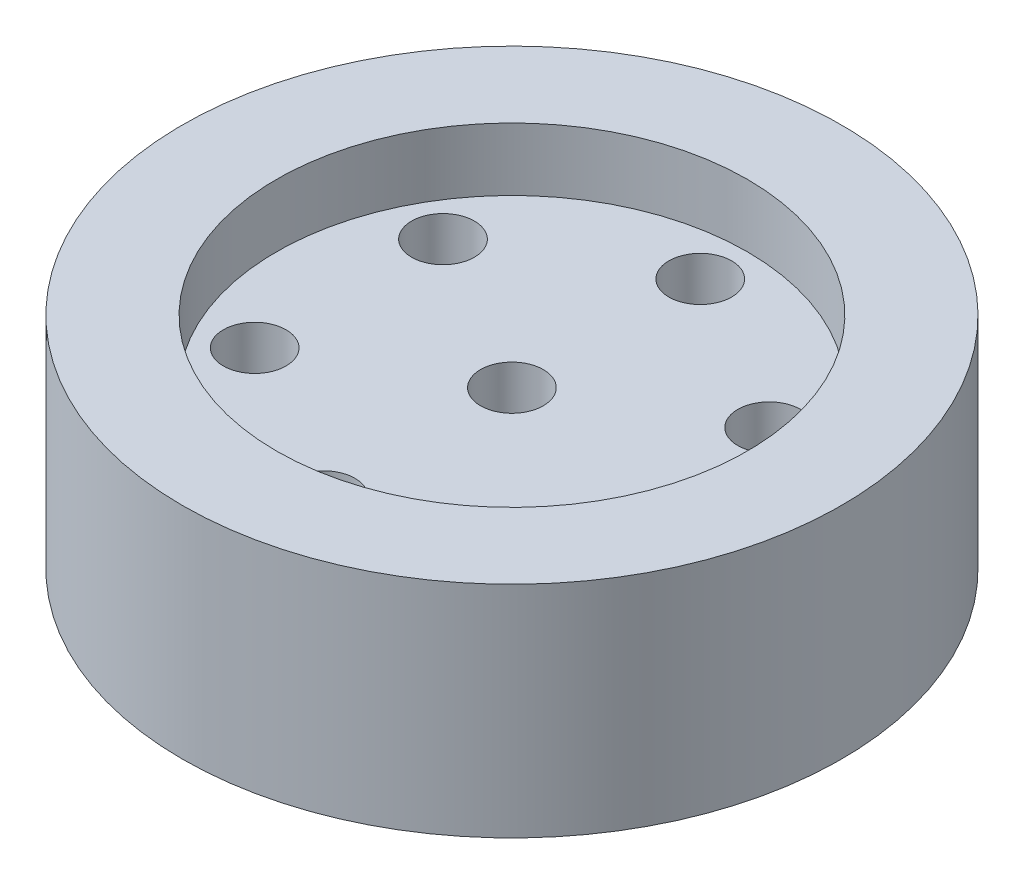
SolidWorks part; units mm, degrees
ref_plane "Front Plane" through (0, 0, 0) normal (0, 0, 1) x (1, 0, 0)
ref_plane "Top Plane" through (0, 0, 0) normal (0, 1, 0) x (1, 0, 0)
ref_plane "Right Plane" through (0, 0, 0) normal (1, 0, 0) x (0, 0, -1)
sketch "Sketch1" plane through (0, 0, 0) normal (0, 1, 0) x (1, 0, 0)
  circle A0 centre (0, 0) radius 21
  dimension "D1" = 42
extrude "Boss-Extrude1" add sketch "Sketch1" along normal blind 14
sketch "Sketch2" plane through (0, 14, 0) normal (0, 1, 0) x (1, 0, 0)
  circle A0 centre (0, 0) radius 15
  dimension "D1" = 30
extrude "Cut-Extrude1" cut sketch "Sketch2" against normal blind 4
sketch "Sketch3" plane through (0, 0, 0) normal (0, -1, 0) x (1, 0, 0)
  circle A0 centre (0, 0) radius 19
  circle A1 centre (0, 0) radius 5
  dimension "D1" = 38
  dimension "D2" = 10
extrude "Cut-Extrude2" cut sketch "Sketch3" against normal blind 4
sketch "Sketch4" plane through (0, 0, 0) normal (0, -1, 0) x (1, 0, 0)
  circle A0 centre (0, 0) radius 2
  dimension "D1" = 4
extrude "Cut-Extrude3" cut sketch "Sketch4" against normal through all
sketch "Sketch5" plane through (0, 4, 0) normal (0, -1, 0) x (1, 0, 0)
  circle A1 centre (0, 0) radius 12 construction
  circle A2 centre (0, 12) radius 2
  circle A3 centre (10.3923, 6) radius 2
  circle A4 centre (10.3923, -6) radius 2
  circle A5 centre (0, -12) radius 2
  circle A6 centre (-10.3923, -6) radius 2
  circle A7 centre (-10.3923, 6) radius 2
  point P18 (0, 0)
  dimension "D1" = 24
  dimension "D2" = 4
  dimension "D3" = 6
extrude "Cut-Extrude4" cut sketch "Sketch5" against normal through all
